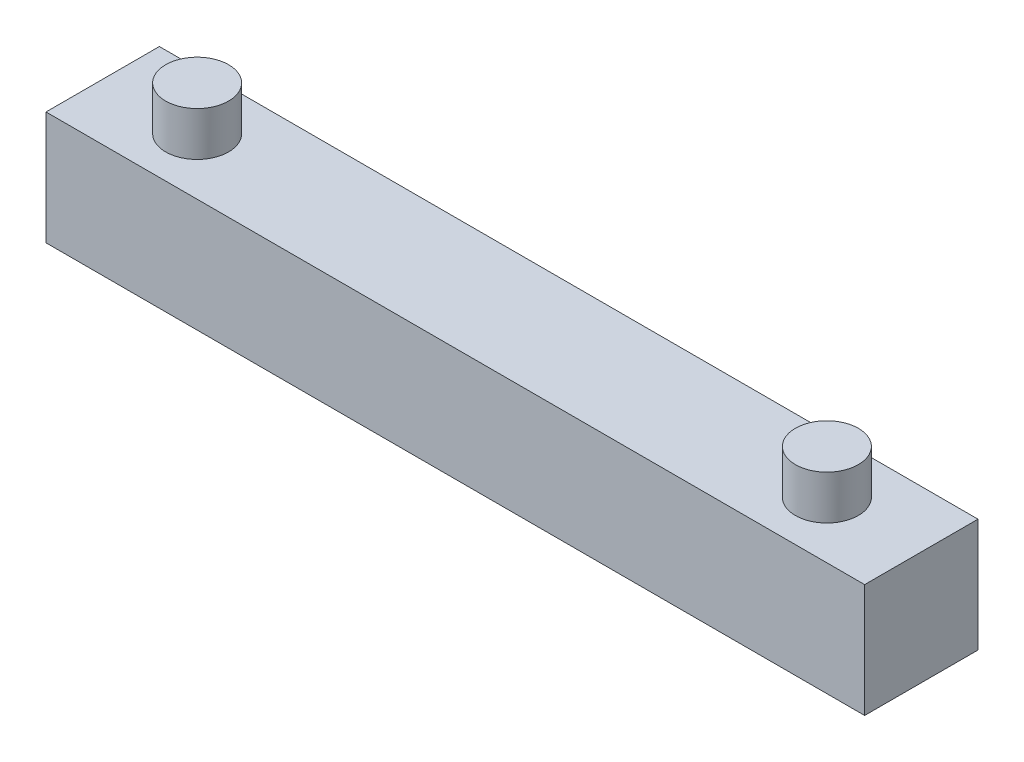
SolidWorks part; units mm, degrees
ref_plane "前基準面" through (0, 0, 0) normal (0, 0, 1) x (1, 0, 0)
ref_plane "上基準面" through (0, 0, 0) normal (0, 1, 0) x (1, 0, 0)
ref_plane "右基準面" through (0, 0, 0) normal (1, 0, 0) x (0, 0, -1)
ref_plane "平面1"
sketch "草圖1" plane through (0, 0, 0) normal (0, 1, 0) x (-1, 0, 0)
  line L0 (32.5, -4.5) -> (-32.5, -4.5)
  line L1 (-32.5, -4.5) -> (-32.5, 4.5)
  line L2 (-32.5, 4.5) -> (32.5, 4.5)
  line L3 (32.5, 4.5) -> (32.5, -4.5)
  dimension "D1" = 65
  dimension "D2" = 9
extrude "擠出1" add sketch "草圖1" along normal blind 9
sketch "草圖2" plane through (0, 9, 0) normal (0, 1, 0) x (-1, 0, 0)
  circle A0 centre (25, 0) radius 2.5
  circle A1 centre (-25, 0) radius 2.5
  dimension "D3" = 5
  dimension "D4" = 5
  dimension "D1" = 25
  dimension "D2" = 25
extrude "擠出2" add sketch "草圖2" along normal blind 3.5 contours A1 | A0
